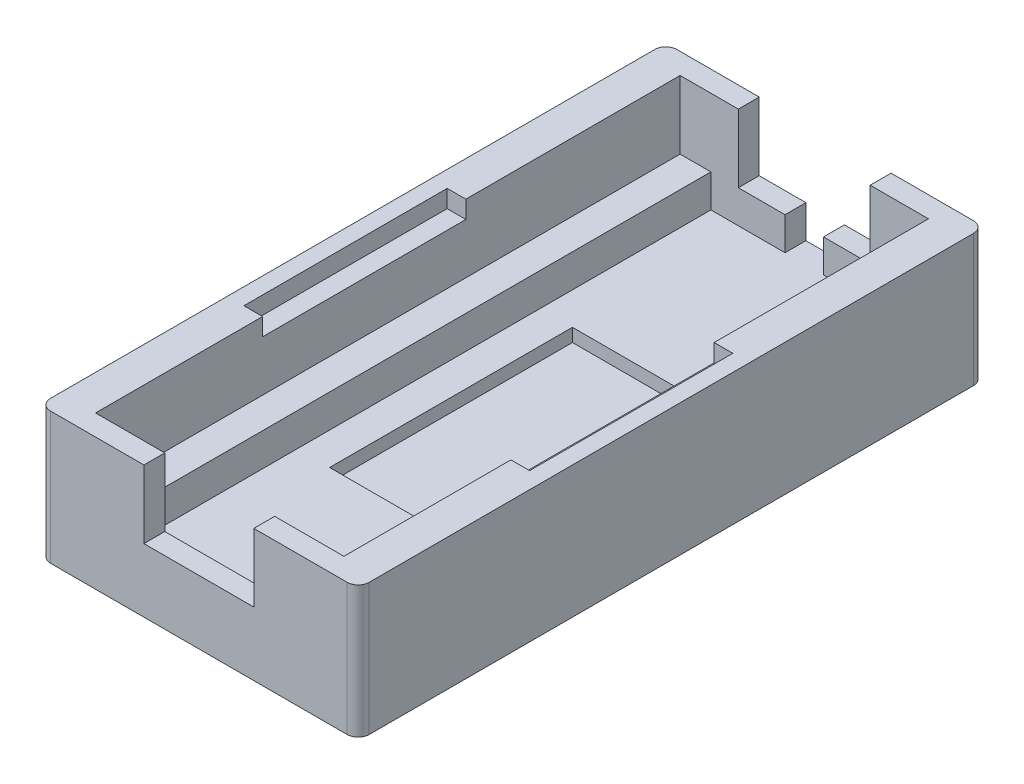
SolidWorks part; units mm, degrees
ref_plane "Front Plane" through (0, 0, 0) normal (0, 0, 1) x (1, 0, 0)
ref_plane "Top Plane" through (0, 0, 0) normal (0, 1, 0) x (1, 0, 0)
ref_plane "Right Plane" through (0, 0, 0) normal (1, 0, 0) x (0, 0, -1)
sketch "Sketch2" plane through (0, 0, 0) normal (0, 1, 0) x (1, 0, 0)
  line L1 (-14.5, 28.5) -> (14.5, 28.5)
  line L2 (-14.5, 28.5) -> (-14.5, -28.5)
  line L3 (-14.5, -28.5) -> (14.5, -28.5)
  line L4 (14.5, 28.5) -> (14.5, -28.5)
  line L5 (-14.5, 28.5) -> (14.5, -28.5) construction
  line L6 (-14.5, -28.5) -> (14.5, 28.5) construction
  point P0 (0, 0)
  dimension "D1" = 57
  dimension "D2" = 29
extrude "Boss-Extrude1" add sketch "Sketch2" along normal blind 12
sketch "Sketch3" plane through (0, 12, 0) normal (0, 1, 0) x (1, 0, 0)
  line L1 (-11.3, 26.6) -> (11.3, 26.6)
  line L2 (-11.3, 26.6) -> (-11.3, -26.6)
  line L3 (-11.3, -26.6) -> (11.3, -26.6)
  line L4 (11.3, 26.6) -> (11.3, -26.6)
  line L5 (-11.3, 26.6) -> (11.3, -26.6) construction
  line L6 (-11.3, -26.6) -> (11.3, 26.6) construction
  point P0 (0, 0)
  dimension "D1" = 22.6
  dimension "D2" = 53.2
extrude "Cut-Extrude1" cut sketch "Sketch3" against normal blind 6.2
sketch "Sketch4" plane through (0, 5.8, 0) normal (0, 1, 0) x (1, 0, 0)
  line L0 (-11.3, -26.6) -> (11.3, -26.6) construction
  line L1 (8.5, 26.6) -> (-8.5, 26.6)
  line L2 (8.5, 26.6) -> (8.5, -26.6)
  line L3 (8.5, -26.6) -> (-8.5, -26.6)
  line L4 (-8.5, 26.6) -> (-8.5, -26.6)
  line L5 (8.5, 26.6) -> (-8.5, -26.6) construction
  line L6 (8.5, -26.6) -> (-8.5, 26.6) construction
  point P0 (0, 0)
  dimension "D1" = 17
extrude "Cut-Extrude2" cut sketch "Sketch4" against normal blind 3
sketch "Sketch5" plane through (0, 2.8, 0) normal (0, 1, 0) x (1, 0, 0)
  line L1 (-5.55, 11.05) -> (5.55, 11.05)
  line L2 (-5.55, 11.05) -> (-5.55, -11.05)
  line L3 (-5.55, -11.05) -> (5.55, -11.05)
  line L4 (5.55, 11.05) -> (5.55, -11.05)
  line L5 (-5.55, 11.05) -> (5.55, -11.05) construction
  line L6 (-5.55, -11.05) -> (5.55, 11.05) construction
  point P0 (0, 0)
  dimension "D1" = 22.1
  dimension "D2" = 11.1
extrude "Cut-Extrude3" cut sketch "Sketch5" against normal blind 1.2
sketch "Sketch6" plane through (0, 12, 0) normal (0, 1, 0) x (1, 0, 0)
  line L0 (0, 28.5) -> (0, -28.5) construction
  line L1 (14.5, 28.5) -> (-14.5, 28.5) construction
  line L2 (-14.5, -28.5) -> (14.5, -28.5) construction
  line L3 (8.5, 26.6) -> (-8.5, 26.6) construction
  line L4 (-13, 7.1) -> (13, 7.1)
  line L5 (-13, 7.1) -> (-13, -11.4)
  line L6 (-13, -11.4) -> (13, -11.4)
  line L7 (13, 7.1) -> (13, -11.4)
  line L8 (-13, 7.1) -> (13, -11.4) construction
  line L9 (-13, -11.4) -> (13, 7.1) construction
  point P6 (0, -2.15)
  dimension "D1" = 26
  dimension "D2" = 18.5
  dimension "D3" = 19.5
extrude "Cut-Extrude4" cut sketch "Sketch6" against normal blind 1.6
sketch "Sketch7" plane through (0, 12, 0) normal (0, 1, 0) x (1, 0, 0)
  line L0 (0, 28.5) -> (0, -28.5) construction
  line L1 (14.5, 28.5) -> (-14.5, 28.5) construction
  line L2 (-14.5, -28.5) -> (14.5, -28.5) construction
  line L3 (11.3, 26.6) -> (-11.3, 26.6) construction
  line L4 (-6, 26.6) -> (6, 26.6)
  line L5 (-6, 26.6) -> (-6, 28.5)
  line L6 (-6, 28.5) -> (6, 28.5)
  line L7 (6, 26.6) -> (6, 28.5)
  line L8 (-6, 26.6) -> (6, 28.5) construction
  line L9 (-6, 28.5) -> (6, 26.6) construction
  line L10 (-5, -26.6) -> (5, -26.6)
  line L11 (-5, -26.6) -> (-5, -28.5)
  line L12 (-5, -28.5) -> (5, -28.5)
  line L13 (5, -26.6) -> (5, -28.5)
  line L14 (-5, -26.6) -> (5, -28.5) construction
  line L15 (-5, -28.5) -> (5, -26.6) construction
  line L16 (-8.5, -26.6) -> (8.5, -26.6) construction
  point P6 (0, 27.55)
  point P11 (0, -27.55)
  dimension "D1" = 12
  dimension "D2" = 10
extrude "Cut-Extrude5" cut sketch "Sketch7" against normal up to surface (6.2 mm away) up to face at (-9.9, 5.8, 0)
fillet "Fillet1" radius 1 4 edges at (14.5, 6, -28.5) (-14.5, 6, -28.5) (14.5, 6, 28.5) (-14.5, 6, 28.5)
sketch "Sketch8" plane through (0, 0, -28.5) normal (0, 0, -1) x (-1, 0, 0)
  line L0 (0, 0) -> (0, 5.8) construction
  line L1 (6, 5.8) -> (-6, 5.8) construction
  line L2 (-8.5, 2.8) -> (8.5, 2.8) construction
  line L3 (-1.75, 5.8) -> (1.75, 5.8)
  line L4 (-1.75, 5.8) -> (-1.75, 2.8)
  line L5 (-1.75, 2.8) -> (1.75, 2.8)
  line L6 (1.75, 5.8) -> (1.75, 2.8)
  line L7 (-1.75, 5.8) -> (1.75, 2.8) construction
  line L8 (-1.75, 2.8) -> (1.75, 5.8) construction
  point P5 (0, 4.3)
  dimension "D1" = 3.5
extrude "Cut-Extrude6" cut sketch "Sketch8" against normal blind 10
